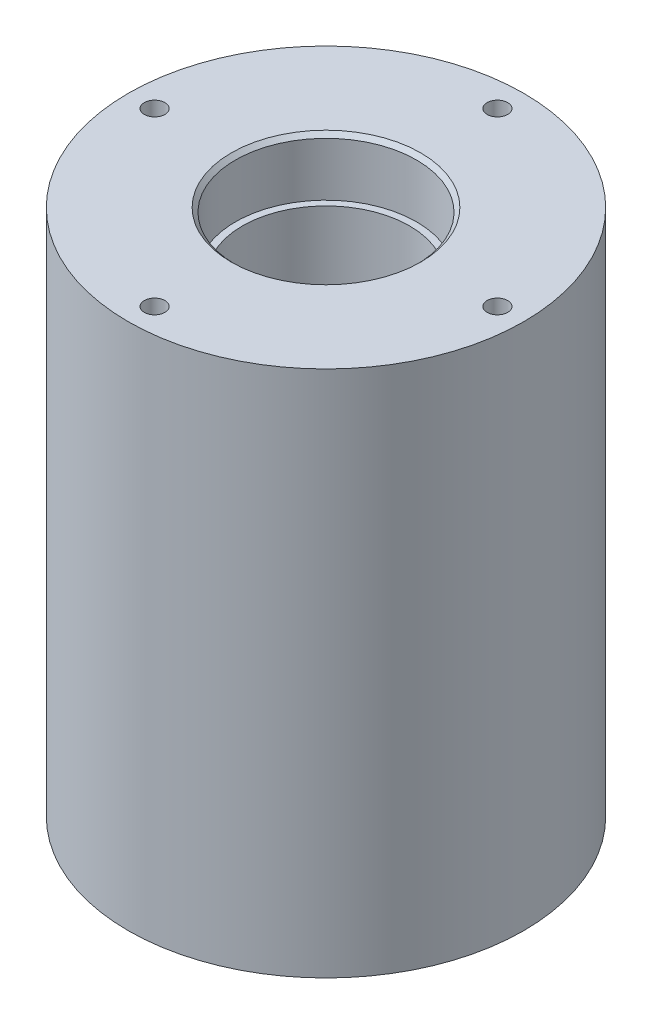
SolidWorks part; units mm, degrees
material "6061 Alloy"
ref_plane "Front Plane" through (0, 0, 0) normal (0, 0, 1) x (1, 0, 0)
ref_plane "Top Plane" through (0, 0, 0) normal (0, 1, 0) x (1, 0, 0)
ref_plane "Right Plane" through (0, 0, 0) normal (1, 0, 0) x (0, 0, -1)
sketch "Sketch4" plane through (0, 0, 0) normal (0, 0, 1) x (1, 0, 0)
  line L0 (0, -13.0821) -> (0, 266.536) construction
  line L1 (10.99, 88.5179) -> (24, 88.5179)
  line L2 (10.99, 88.5179) -> (10.99, 81.5179)
  line L3 (10.99, 24.5179) -> (24, 24.5179)
  line L4 (24, 88.5179) -> (24, 24.5179)
  line L5 (82.5, 31.5179) -> (-82.5, 31.5179) construction
  line L6 (82.5, 88.5179) -> (-82.5, 88.5179) construction
  line L7 (0, 100.5179) -> (0, -13.0821) construction
  line L8 (82.5, 100.5179) -> (-82.5, 100.5179) construction
  line L9 (82.5, 24.5179) -> (-82.5, 24.5179) construction
  line L10 (82.5, 81.5179) -> (-82.5, 81.5179) construction
  line L11 (-10, 13.9179) -> (10, 13.9179) construction
  line L12 (10.14, 81.5179) -> (10.99, 81.5179)
  line L13 (10.99, 31.5179) -> (10.99, 24.5179)
  line L14 (10.14, 81.5179) -> (10.14, 31.5179)
  line L15 (10.14, 31.5179) -> (10.99, 31.5179)
  dimension "D2" = 64
  dimension "D3" = 10.99
  dimension "D4" = 7
  dimension "D7" = 20
  dimension "D5" = 10.14
  dimension "D6" = 50
  dimension "D1" = 24
revolve "Revolve1" add sketch "Sketch4" angle 360 about L7
sketch "Sketch5" plane through (0, 88.5179, 0) normal (0, 1, 0) x (1, 0, 0)
  circle A0 centre (0, 0) radius 20.8 construction
  circle A1 centre (20.8, 0) radius 1.25
  circle A2 centre (0, 20.8) radius 1.25
  circle A3 centre (0, 0) radius 20.8 construction
  circle A4 centre (0, -20.8) radius 1.25
  circle A5 centre (0, 0) radius 20.8 construction
  circle A7 centre (0, 0) radius 20.8 construction
  circle A9 centre (0, 0) radius 20.8 construction
  circle A11 centre (0, 0) radius 20.8 construction
  circle A12 centre (0, -20.8) radius 1.25 [skipped]
  circle A13 centre (20.8, 0) radius 1.25 [skipped]
  circle A14 centre (-20.8, 0) radius 1.25 [skipped]
  circle A15 centre (-20.8, 0) radius 1.25
  circle A16 centre (0, 0) radius 20.8 construction
  point P19 (0, 0)
  point P27 (0, 0)
  dimension "D2" = 2.5
  dimension "D1" = 41.6
  dimension "D3" = 4
  dimension "D4" = 4
chamfer "Chamfer1" distance 0.5 angle 45 2 edges at (0, 24.5179, 10.99) (0, 88.5179, 10.99)
extrude "Cut-Extrude2" cut sketch "Sketch5" against normal blind 6
sketch "Sketch6" plane through (0, 24.5179, 0) normal (0, -1, 0) x (1, 0, 0)
  circle A0 centre (0, 0) radius 20.8 construction
  circle A1 centre (0, 20.8) radius 1.25
  circle A2 centre (0, 0) radius 20.8 construction
  circle A3 centre (20.8, 0) radius 1.25
  circle A4 centre (-20.8, 0) radius 1.25
  circle A5 centre (0, 0) radius 20.8 construction
  circle A6 centre (0, -20.8) radius 1.25
  circle A7 centre (0, 0) radius 20.8 construction
  point P17 (0, 0)
  dimension "D2" = 2.5
  dimension "D1" = 41.6
  dimension "D3" = 4
extrude "Cut-Extrude3" cut sketch "Sketch6" against normal blind 6
equation "\"D3@Sketch4\"=\"HUB_BearingSeatDia\"/2"
equation "\"D5@Sketch4\"=\"HUB_BridgeStopDia\"/2"
equation "\"D2@Sketch5\"=\"HUB_RetainerTapDia\""
equation "\"D1@Sketch5\"=\"HUB_RetainerBCDia\""
equation "\"D1@Sketch4\"=\"HUB_MainBodyOD\"/2"
equation "\"D1@Cut-Extrude2\"=\"HUB_RetainerBlindHoleDepth\""
equation "\"D1@Sketch6\"=\"HUB_RetainerBCDia\""
equation "\"D2@Sketch6\"=\"HUB_RetainerTapDia\""
equation "\"D1@Cut-Extrude3\"=\"HUB_RetainerBlindHoleDepth\""
equation "\"____ VERSION / MIRROR CONTROL ____\" = 0"
equation "\"SYS_VersionTag\" = 2.00"
equation "\"HUB_IsMachinedMetal\" = 1"
equation "\"____ BEARING BLOCK ____\" = 0"
equation "\"BRG_BearingOD\" = 22mm"
equation "\"BRG_BearingWidth\" = 7mm"
equation "\"BRG_InnerRingSpacing\" = 50mm"
equation "\"____ FIXED SHAFT / INNER-RING HARDWARE ____\" = 0"
equation "\"HW_WasherThk\" = 1.6mm"
equation "\"HW_CollarOD\" = 20mm"
equation "\"HW_CollarWidth\" = 9mm"
equation "\"REQ_LowerHardwareHeight\" = \"HW_WasherThk\" + \"HW_CollarWidth\""
equation "\"BRG_ClearanceBelowLowerHardware\" = 2mm"
equation "\"____ HUB SEATS + BRIDGE ____\" = 0"
equation "\"HUB_OuterRingSeatFitOffsetDia\" = IIF(\"HUB_IsMachinedMetal\" > 0, 0.02mm, -0.05mm)"
equation "\"HUB_OuterRingSeatDia\" = \"BRG_BearingOD\" - \"HUB_OuterRingSeatFitOffsetDia\""
equation "\"HUB_OuterRingSeatAxialDepth\" = \"BRG_BearingWidth\""
equation "\"HUB_MainBodyOD\" = 48mm"
equation "\"HUB_SeatToSeatBridgeLen\" = \"BRG_InnerRingSpacing\""
equation "\"____ HUB INNER STOP + LOWER HARDWARE RELIEF ____\" = 0"
equation "\"HUB_BridgeStopRadialClearOverLowerHardware\" = 0.14mm"
equation "\"HUB_BridgeStopDia\" = \"HW_CollarOD\" + 2*\"HUB_BridgeStopRadialClearOverLowerHardware\""
equation "\"HUB_LowerHardwareReliefRequiredDepth\" = \"REQ_LowerHardwareHeight\" + \"BRG_ClearanceBelowLowerHardware\" + 0.5mm"
equation "\"HUB_LowerHardwareReliefDepthMargin\" = 0.5mm"
equation "\"HUB_LowerHardwareReliefDepth\" = \"HUB_LowerHardwareReliefRequiredDepth\" + \"HUB_LowerHardwareReliefDepthMargin\""
equation "\"HUB_MainBodyBelowLowerSeatDepth\" = \"HUB_LowerHardwareReliefDepth\""
equation "\"____ HUB RETAINERS + DECK INTERFACE ____\" = 0"
equation "\"HUB_RetainerScrewSize\" = 3mm"
equation "\"HUB_RetainerScrewCount\" = 4"
equation "\"HUB_RetainerClearDia\" = 3.4mm"
equation "\"HUB_RetainerTapDia\" = 2.5mm"
equation "\"HUB_RetainerEdgeMin\" = 1.5mm"
equation "\"HUB_RetainerBoltR\" = (\"HUB_MainBodyOD\" / 2) - (\"HUB_RetainerClearDia\" / 2) - \"HUB_RetainerEdgeMin\""
equation "\"HUB_RetainerBCDia\" = 2*\"HUB_RetainerBoltR\""
equation "\"____ HUB RETAINER THREAD / BLIND-HOLE MACHINING INTENT ____\" = 0"
equation "\"HUB_RetainerHoleStyle_Blind\" = 1"
equation "\"HUB_RetainerThreadEngagementMin\" = 3.0mm"
equation "\"HUB_RetainerThreadEngagementTarget\" = 4.5mm"
equation "\"HUB_RetainerBottomDrillAllowance\" = 1.5mm"
equation "\"HUB_RetainerBlindHoleDepth\" = \"HUB_RetainerThreadEngagementTarget\" + \"HUB_RetainerBottomDrillAllowance\""
equation "\"HUB_RetainerTapDepth\" = \"HUB_RetainerBlindHoleDepth\""
equation "\"HUB_RetainerMaxUsableThreadDepth\" = \"HUB_RetainerBlindHoleDepth\" - \"HUB_RetainerBottomDrillAllowance\""
equation "\"HUB_RetainerScrewIntoHubTarget\" = \"HUB_RetainerThreadEngagementTarget\""
equation "\"HUB_RetainerScrewIntoHubMin\" = \"HUB_RetainerThreadEngagementMin\""
equation "\"HUB_DeckMountCount\" = 4"
equation "\"HUB_DeckMountClearDia\" = 4.5mm"
equation "\"HUB_DeckMountBCDia\" = 58mm"
equation "\"____ HUB VARIABLE COMPATIBILITY ALIASES (KEEP v2.00 MAP STABLE) ____\" = 0"
equation "\"HUB_BearingSeatDia\" = \"HUB_OuterRingSeatDia\""
equation "\"HUB_BearingSeatDepth\" = \"HUB_OuterRingSeatAxialDepth\""
equation "\"HUB_BodyOD\" = \"HUB_MainBodyOD\""
equation "\"HUB_SeatBridgeLen\" = \"HUB_SeatToSeatBridgeLen\""
equation "\"HUB_LowerClearanceDia\" = \"HUB_BridgeStopDia\""
equation "\"HUB_LowerOverallDepth\" = \"HUB_MainBodyBelowLowerSeatDepth\""
equation "\"HUB_LowerClearancePocketDepth\" = \"HUB_LowerHardwareReliefDepth\""
equation "\"____ SANITY CHECKS ____\" = 0"
equation "\"CHK_HubRetainerHoleStyleBlind\" = \"HUB_RetainerHoleStyle_Blind\""
equation "\"CHK_HubRetainerThreadEngagementMeetsMin\" = \"HUB_RetainerThreadEngagementTarget\" - \"HUB_RetainerThreadEngagementMin\""
equation "\"CHK_HubRetainerBlindHoleDepthPositive\" = \"HUB_RetainerBlindHoleDepth\""
equation "\"CHK_HubRetainerUsableThreadDepthMeetsMin\" = \"HUB_RetainerMaxUsableThreadDepth\" - \"HUB_RetainerThreadEngagementMin\""
equation "\"OUT_HubRetainerTapHoleCenterRadius\" = \"HUB_RetainerBCDia\" / 2"
equation "\"OUT_HubRetainerTapHoleInnerEdgeRadius\" = \"OUT_HubRetainerTapHoleCenterRadius\" - (\"HUB_RetainerTapDia\" / 2)"
equation "\"OUT_HubSeatOuterRadius\" = \"HUB_BearingSeatDia\" / 2"
equation "\"OUT_HubBridgeStopOuterRadius\" = \"HUB_LowerClearanceDia\" / 2"
equation "\"CHK_HubRetainerTapHoleOutsideSeat\" = \"OUT_HubRetainerTapHoleInnerEdgeRadius\" - \"OUT_HubSeatOuterRadius\""
equation "\"CHK_HubRetainerTapHoleOutsideBridgeStop\" = \"OUT_HubRetainerTapHoleInnerEdgeRadius\" - \"OUT_HubBridgeStopOuterRadius\""
